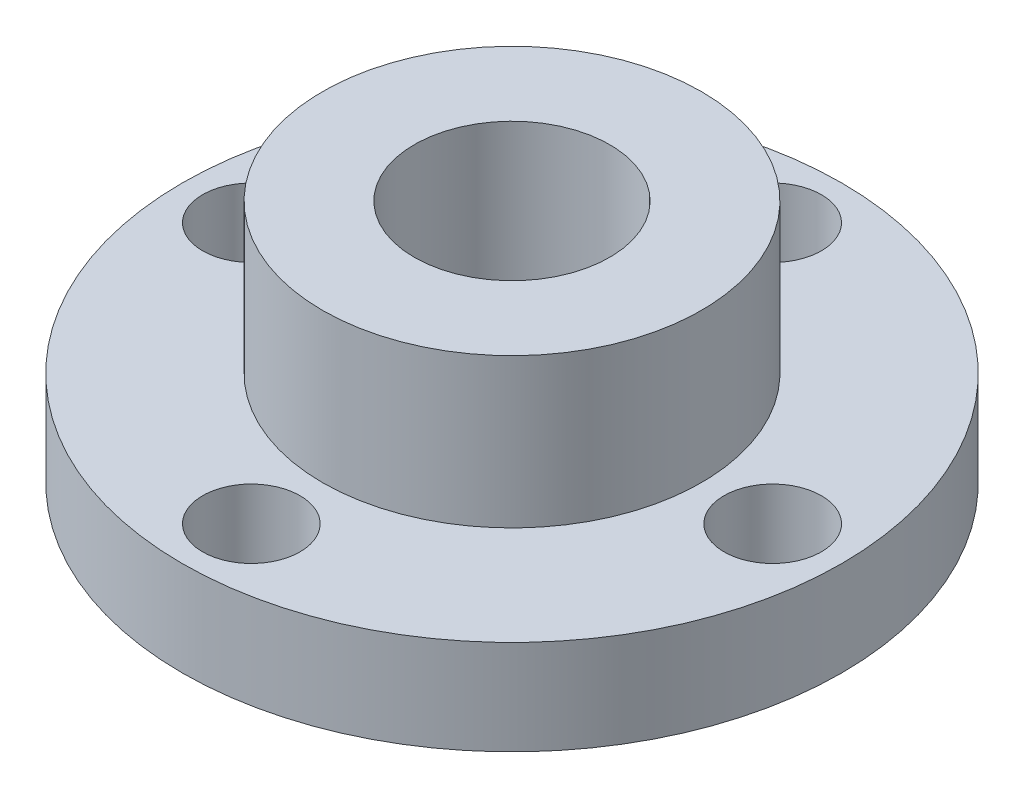
SolidWorks part; units mm, degrees
material "6061-T6 (SS)"
ref_plane "Front Plane" through (0, 0, 0) normal (0, 0, 1) x (1, 0, 0)
ref_plane "Top Plane" through (0, 0, 0) normal (0, 1, 0) x (1, 0, 0)
ref_plane "Right Plane" through (0, 0, 0) normal (1, 0, 0) x (0, 0, -1)
sketch "Sketch1" plane through (0, 0, 0) normal (0, 1, 0) x (1, 0, 0)
  line L0 (0, 0) -> (6.5484, 0) construction
  line L4 (0, 0) -> (-19.05, 0) construction
  circle A0 centre (0, 0) radius 4.826
  circle A1 centre (0, 0) radius 6.5484 construction
  arc A2 (3.9286, 10.8597) -> (3.9286, -10.8597) centre (0, 0) ccw construction
  circle A3 centre (0, 0) radius 22.098
  circle A5 centre (0, 0) radius 11.5484 construction
  circle A6 centre (-19.05, 0) radius 2.9766 construction
  dimension "D1" = 9.652
  dimension "D2" = 13.0969
  dimension "D3" = 23.0969
  dimension "D7" = 5.9531
  dimension "D5" = 44.196
  dimension "D4" = 19.05
extrude "main body" add sketch "Sketch1" along normal blind 6.35
sketch "Sketch2" plane through (0, 6.35, 0) normal (0, 1, 0) x (1, 0, 0)
  circle A0 centre (0, 0) radius 12.7
  circle A2 centre (0, 0) radius 6.5484
  dimension "D1" = 13.0969
  dimension "D2" = 25.4
extrude "tap boss" add sketch "Sketch2" along normal blind 10
hole_wizard "M6 Clearance Hole1" positions "Sketch3" profile "Sketch4" hole size "M6" standard "ANSI Metric"
sketch "Sketch3" plane through (0, 6.35, 0) normal (0, 1, 0) x (1, 0, 0)
  point P0 (-19.05, 0)
  point P7 (-9.525, 16.4978)
  point P8 (9.525, 16.4978)
  point P9 (19.05, 0)
  point P10 (9.525, -16.4978)
  point P11 (-9.525, -16.4978)
  point P12 (0, 0)
  dimension "D1" = 6
sketch "Sketch4" plane through (-19.05, 6.35, 0) normal (1, 0, 0) x (0, 0, 1)
  line L0 (0, 0) -> (0, 6.35)
  line L1 (0, 6.35) -> (3.2, 6.35)
  line L2 (3.2, 6.35) -> (3.2, 0)
  line L5 (3.2, 0) -> (0, 0)
  line L11 (0, -6.35) -> (0, 107.95) construction
  dimension "Thru Hole Dia." = 6.4
  dimension "Thru Hole Depth" = 6.35
sketch "Sketch5" plane through (0, 0, 0) normal (0, -1, 0) x (1, 0, 0)
  line L0 (0, 0) -> (-22.098, 0) construction
  line L1 (-22.098, 0) -> (-22.098, 22.098) construction
  line L2 (-22.098, 22.098) -> (0, 22.098) construction
  line L3 (0, 22.098) -> (0, 0) construction
  circle A0 centre (0, 0) radius 22.098 construction
sketch "Sketch6" plane through (0, 6.35, 0) normal (0, 1, 0) x (1, 0, 0)
  circle A0 centre (-17.4724, 0) radius 3.2639
extrude "Cut-Extrude1" cut sketch "Sketch6" against normal through all
pattern_circular "CirPattern1" count 4 over 360 about axis through (0, 0, 0) along (0, 1, 0) of "Cut-Extrude1"
equation "\"z\"= 8\t\t\t\t'number of blades"
equation "\"de\"= 0.43in\t\t\t'entrance eye diameter"
equation "\"de_length\"= 4mm\t\t'entrance eye consistent length"
equation "\"d_exit\"= 0.18in \t\t'throat aka d1"
equation "\"d2\"= 2.1in \t\t\t'outer diameter of the impeller"
equation "\"b2\"= .2in\t\t\t'tip height from disc surface at d2; slightly higher than d_exit"
equation "\"b1\"= \"b2\" + (\"d2\"/2 - \"de\"/2)*tan(\"theta\") \t\t\t'tip height from disc surface at inlet eye"
equation "\"theta\"= 12\t\t\t'angle of blades from inner to outer "
equation "\"ae\"= 3.14*(\"de\"^2)/4\t\t'entrance eye area'"
equation "\"ce\"= 3.14*\"de\"\t\t'entrance eye circumference"
equation "\"av_ratio\"= .325\t\t'ratio of av/ae at N_s of 470, range is .275 to .375, .325 ideal. High ratio means bigger area means smaller blades"
equation "\"av\"= \"ae\"*\"av_ratio\"\t\t'area between just two blades"
equation "\"s_open\"= \"av\"/\"b1\"\t\t'width of open area"
equation "\"s\"=\"ce\" - \"z\"*\"s_open\""
equation "\"min blade thickness\"= .15in"
equation "\"bearing OD\"= 30mm"
equation "\"bearing ID\"= 10mm"
equation "\"bearing depth\"= 9mm"
equation "\"bearing outer race thickness\"= 1mm"
equation "\"bearing inner race thickness\"= 1mm"
equation "\"bearing bore\"= \"bearing depth\" + 1mm"
equation "\"lower seal OD\"= .917in\t\t'this is https://www.mcmaster.com/#9281k121/=174001b"
equation "\"lower seal ID\"= .375in"
equation "\"lower seal depth\"= .625in + .218in"
equation "\"lower seal bore\"= \"lower seal depth\" + 1mm"
equation "\"upper seal OD\"= 1.125in\t'this is https://www.mcmaster.com/#5154t33/=173zuau, needs to be visually inspected before machining!"
equation "\"upper seal ID\"= 0.625in"
equation "\"upper seal depth\"= .25in\t'aka height; these values need to be confirmed by inspection!! We may want to compress the height."
equation "\"upper seal bore\"= \"upper seal depth\" + 1mm"
equation "\"big o-ring thickness\"= .139in"
equation "\"big o-ring OD\"= 2.734in"
equation "\"big o-ring ID\"= 3.012in"
equation "\"big o-ring groove depth\"= \"big o-ring thickness\"*4/5"
equation "\"impeller center height\"= \"impeller base thickness\" + \"b1\"\t'impeller height at de"
equation "\"impeller outer height\"= \"impeller base thickness\" + \"b2\"\t'impeller height at de"
equation "\"impeller upper clearance\"= .5mm"
equation "\"impeller horizontal clearance\"= (\"d2\"*1.15 - \"d2\")/2 \t\t'clearance based on D2-D3 ratio for circular volute, ranges 1.15 to 1.2"
equation "\"impeller bottom clearance\"= .5mm"
equation "\"impeller base thickness\"= 2mm"
equation "\"impeller dowel diameter\"= 2mm"
equation "\"impeller bolt head diameter\"= \"m4 head bore diameter\""
equation "\"impeller bolt head depth\"= 4mm"
equation "\"impeller bolt stop depth\"= 3mm"
equation "\"impeller bolt bore\"= \"m4 clearance\""
equation "\"impeller shaft bore depth\"= 12mm"
equation "\"impeller shaft bore\"= 8mm"
equation "\"impeller boss depth\"= \"impeller shaft bore depth\"+\"impeller bolt stop depth\"+\"impeller bolt head depth\"-\"impeller base thickness\""
equation "\"impeller boss diameter\"= \"upper seal ID\""
equation "\"impeller dowel length\"= 2mm*2 + \"impeller shaft bore\""
equation "\"coupler motor shaft hole ID\"= 8mm"
equation "\"coupler OD\"= 17mm"
equation "\"coupler length\"= 25mm"
equation "\"motor OD\"= 64mm"
equation "\"motor shaft diameter\"= 8mm"
equation "\"motor shaft pride\"= 32mm"
equation "\"motor to bearing plate distance\"= \"motor shaft pride\" + 2mm +\"coupler length\"/2"
equation "\"square plate bolt bore\"= \"m8 clearance\""
equation "\"square plate bolt head diameter\"= 13.5mm"
equation "\"square plate bolt head depth\"= 8mm"
equation "\"square plate bolt pattern diameter\"= 3.5in"
equation "\"motor mount center bore\"= \"coupler OD\"+ 4mm"
equation "\"motor mount post radius\"= ( 3 * \"square plate bolt bore\" ) / 2"
equation "\"motor mount m4 screw hole diameter\"= 4mm"
equation "\"motor mount m4 head diameter\"= 7.25mm"
equation "\"motor mount m4 head depth\"= 4mm"
equation "\"motor mount m4 pattern diamater\"= 30mm"
equation "\"motor mount plate thickness\"= 8mm + \"motor mount m4 head depth\""
equation "\"bearing plate stop ID\"= \"bearing OD\" - 4mm"
equation "\"bearing plate stop depth\"= 3mm"
equation "\"bearing plate thickness\"= \"bearing bore\" + \"bearing plate stop depth\" + \"shaft bearing stop length\""
equation "\"lower seal plate lip depth\"= 2mm"
equation "\"lower seal plate lip ID\"= \"lower seal OD\" - 3mm"
equation "\"lower seal plate thickness\"= \"lower seal plate lip depth\" + \"lower seal bore\""
equation "\"shaft coupler section diameter\"= 8mm"
equation "\"shaft coupler section length\"= \"motor to bearing plate distance\" - \"motor shaft pride\" - 2mm"
equation "\"shaft bearing section diameter\"= \"bearing ID\""
equation "\"shaft bearing section length\"= \"bearing plate stop depth\" + \"bearing depth\""
equation "\"shaft bearing stop diameter\"= \"bearing ID\" + 4mm"
equation "\"shaft bearing stop length\"= 3mm"
equation "\"shaft lower seal section diameter\"= \"lower seal ID\""
equation "\"shaft lower seal section length\"= \"lower seal plate thickness\" + 1mm"
equation "\"shaft impeller section diameter\"= \"impeller shaft bore\""
equation "\"shaft impeller section length\"= \"upper seal plate thickness\" + \"upper seal plate riser\" + \"impeller bottom clearance\" + \"impeller base thickness\" - \"impeller bolt head depth\" - \"impeller bolt stop depth\""
equation "\"upper seal plate thickness\"= \"upper seal plate pressure hole diameter\"+10mm"
equation "\"upper seal plate lip ID\"= \"upper seal OD\" - 3mm"
equation "\"upper seal plate riser\"= 6.59mm \t\t'this number needs to be read from the housing file"
equation "\"upper seal plate pressure hole diameter\"= .125in\t'this is 1/8 drill "
equation "\"upper seal plate pressure tap diameter\"= .328125in \t'this is 21/64 drill for a 1/8 ANPT tap"
equation "\"upper seal plate pressure tap grip\"= 5mm\t\t'this is the area around the tap so it doesn't crack"
equation "\"upper seal plate pressure tap depth\"= 12mm"
equation "\"impeller cavity center height\"= \"impeller bottom clearance\" + \"impeller upper clearance\" + \"impeller center height\""
equation "\"impeller cavity diameter\"= 2 * \"impeller horizontal clearance\" + \"d2\" \t\t\t\t\t\t\t\t\t'called D3 analytically"
equation "\"impeller cavity outer height\"= \"impeller bottom clearance\" + \"impeller upper clearance\" + \"impeller base thickness\" + \"b2\" \t\t'this is height at impeller diameter d2, not at d3"
equation "\"impeller housing thickness\"= \"impeller housing exit threaded diameter\" + 2*\"impeller housing outlet grip\""
equation "\"impeller housing diameter\"= 4.5in"
equation "\"impeller housing bolt count\"= 8"
equation "\"impeller housing bolt diameter\"= \"m6 clearance\""
equation "\"impeller housing bolt pattern diameter\"= 3.5in"
equation "\"impeller housing threaded inlet diameter\"= 0.71875in \t'this is the 23/32 drill size for 1/2 NPT fitting https://www.mcmaster.com/#50715k269/=176pljy"
equation "\"impeller housing threaded inlet depth\"= .6in"
equation "\"impeller housing exit threaded diameter\"= 0.515625in \t\t'this is the 33/64 drill size for 9/16-18 fitting, expecting swagelok SS-8FK0-1-6STH fitting"
equation "\"impeller housing exit threaded depth\"= 10mm"
equation "\"impeller housing diffuser conical angle\"=10"
equation "\"impeller housing diffuser tangent angle\"=5"
equation "\"impeller housing diffuser final diameter\"= .38in\t\t'aka d2'"
equation "\"impeller housing outlet grip\"= 5mm"
equation "\"end mill size\"= 0.375in\t'for 3/8 endmill"
equation "\"m4 clearance\"= 0.171875in \t'this is 11/64 bit for 4.36mm"
equation "\"m4 tap\"= 0.125in\t\t'this is 1/8 bit for 3.17mm"
equation "\"m4 head bore diameter\"= 7.5mm"
equation "\"m4 head bore depth\"= 5mm\t'actual is ~4mm"
equation "\"m6 clearance\"= 0.234375in\t'this is 15/64 bit = 5.95mm, could use 6mm bit, B bit for 6.04mm or 1/4 bit for 6.35mm"
equation "\"m6 tap\"= 5mm\t\t\t'5mm is appropriate, could use 13/64 or #5,6,7"
equation "\"m6 head bore diameter\"= 11mm\t\t"
equation "\"m6 head bore depth\"= 7mm\t'actual is 6mm"
equation "\"m8 clearance\"= 0.3125in\t'this is 5/16in for 7.93mm, could use 8mm, O,P, or 21/64"
equation "\"m8 tap\"= 0.265625in\t\t'this is 17/64 for 6.746875mm"
equation "\"m8 head bore diameter\"= 14mm"
equation "\"m8 head bore depth\"= 9mm\t'actual is 8mm"
equation "\"D1@Sketch1\"=\"impeller housing diffuser final diameter\""
equation "\"D2@Sketch1\"=\"impeller housing exit threaded diameter\""
equation "\"D3@Sketch1\"=\"impeller housing exit threaded diameter\"+\"impeller housing outlet grip\"*2 "
equation "\"D7@Sketch1\"=\"m6 clearance\""
equation "\"D1@Sketch2\"=\"impeller housing exit threaded diameter\""
equation "\"D1@tap boss\" = 10mm"
equation "\"diffuser cartridge OD\"=.75in"
equation "\"diffuser flange bolt pattern diameter\"= 1.4in"
equation "\"D4@Sketch1\"=.75in"
